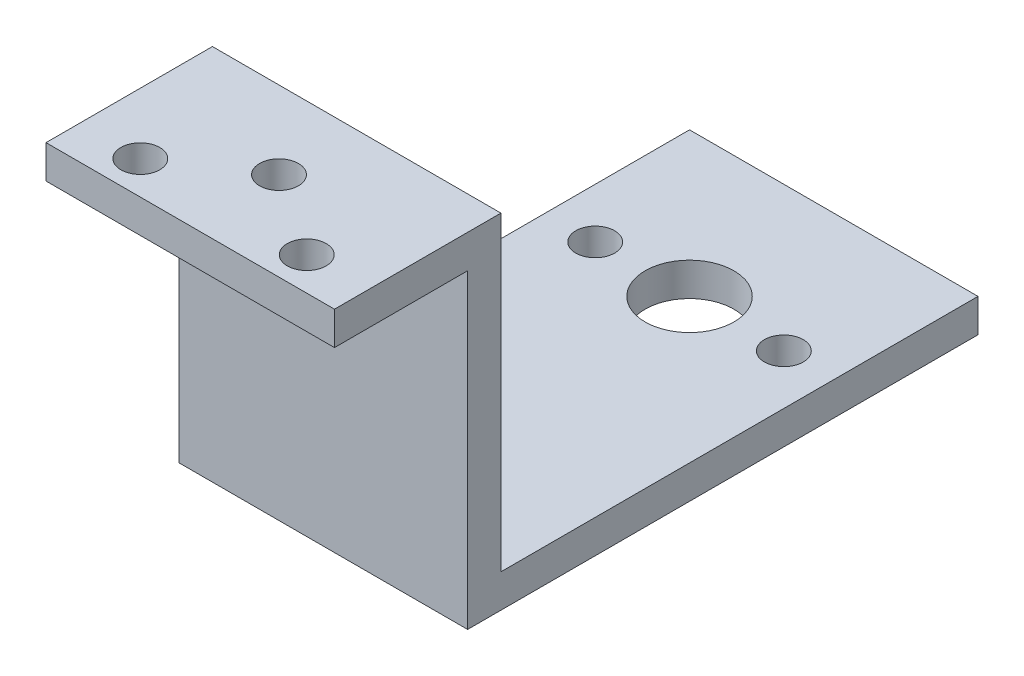
SolidWorks part; units mm, degrees
ref_plane "前视基准面" through (0, 0, 0) normal (0, 0, 1) x (1, 0, 0)
ref_plane "上视基准面" through (0, 0, 0) normal (0, 1, 0) x (1, 0, 0)
ref_plane "右视基准面" through (0, 0, 0) normal (1, 0, 0) x (0, 0, -1)
sketch "草图1" plane through (0, 0, 0) normal (0, 1, 0) x (1, 0, 0)
  line L0 (-13, 0) -> (-13, -30)
  line L1 (-13, -30) -> (13, -30)
  line L2 (13, -30) -> (13, 0)
  arc A0 (13, 0) -> (-13, 0) centre (0, 0) ccw
  circle A1 centre (0, 0) radius 4
  circle A2 centre (8.5, 0) radius 1.75
  circle A3 centre (-8.5, 0) radius 1.75
  point P9 (0, 0)
  dimension "D1" = 26
  dimension "D2" = 8
  dimension "D4" = 3.5
  dimension "D5" = 3.5
  dimension "D3" = 17
  dimension "D6" = 30
extrude "凸台-拉伸1" add sketch "草图1" along normal blind 3
sketch "草图4" plane through (13, 0, 0) normal (1, 0, 0) x (0, 0, -1)
  line L0 (-30, 3) -> (-30, 31)
  line L1 (-30, 31) -> (-45, 31)
  line L2 (-45, 31) -> (-45, 28)
  line L3 (-45, 28) -> (-33, 28)
  line L4 (-33, 28) -> (-33, 0)
  line L5 (-33, 0) -> (-30, 0)
  line L10 (-30, 0) -> (0, 0)
  line L11 (0, 0) -> (0, 3)
  line L12 (0, 3) -> (-30, 3)
  line L13 (-30, 3) -> (-30, 0)
  line L17 (-30, 3) -> (-30, 0)
  dimension "D1" = 3
  dimension "D2" = 28
  dimension "D3" = 15
  dimension "D4" = 3
  dimension "D5" = 0
extrude "凸台-拉伸2" add sketch "草图4" against normal up to surface (26 mm away) up to face at (-13, 1.5, 15)
sketch "草图6" plane through (0, 28, 0) normal (0, -1, 0) x (1, 0, 0)
  line L0 (-13, 33) -> (13, 33) construction
  line L1 (-7.5, 42) -> (7.5, 42)
  line L2 (-7.5, 42) -> (-7.5, 37)
  line L3 (-7.5, 37) -> (7.5, 37)
  line L4 (7.5, 42) -> (7.5, 37)
  line L5 (-7.5, 42) -> (7.5, 37) construction
  line L6 (-7.5, 37) -> (7.5, 42) construction
  line L7 (-13, 45) -> (13, 45) construction
  line L8 (0, 45) -> (0, 34.8657) construction
  circle A0 centre (-7.5, 42) radius 1.75
  circle A1 centre (7.5, 42) radius 1.75
  circle A2 centre (0, 37) radius 1.75
  point P0 (0, 39.5)
  point P7 (0, 45)
  dimension "D4" = 3.5
  dimension "D1" = 4
  dimension "D2" = 5
  dimension "D3" = 15
extrude "切除-拉伸1" cut sketch "草图6" against normal through all contours L4 A1 L1 | L1 A1 L4 | L3 A2 | L3 A2 | L2 A0 L1 | L1 A0 L2
sketch "草图7" plane through (0, 0, 0) normal (0, -1, 0) x (1, 0, 0)
  line L0 (-13, 0) -> (-13, -13)
  line L1 (-13, -13) -> (13, -13)
  line L2 (13, -13) -> (13, 0)
  arc A0 (-13, 0) -> (13, 0) centre (0, 0) ccw construction
  arc A1 (-13, 0) -> (13, 0) centre (0, 0) ccw
  arc M1 (-13, 0) -> (13, 0) centre (0, 0) ccw
extrude "凸台-拉伸4" add sketch "草图7" against normal up to surface (3 mm away) contours L0 L1 M1 | L1 L2 M1 up to face at (8.5, 3, 1.75)
